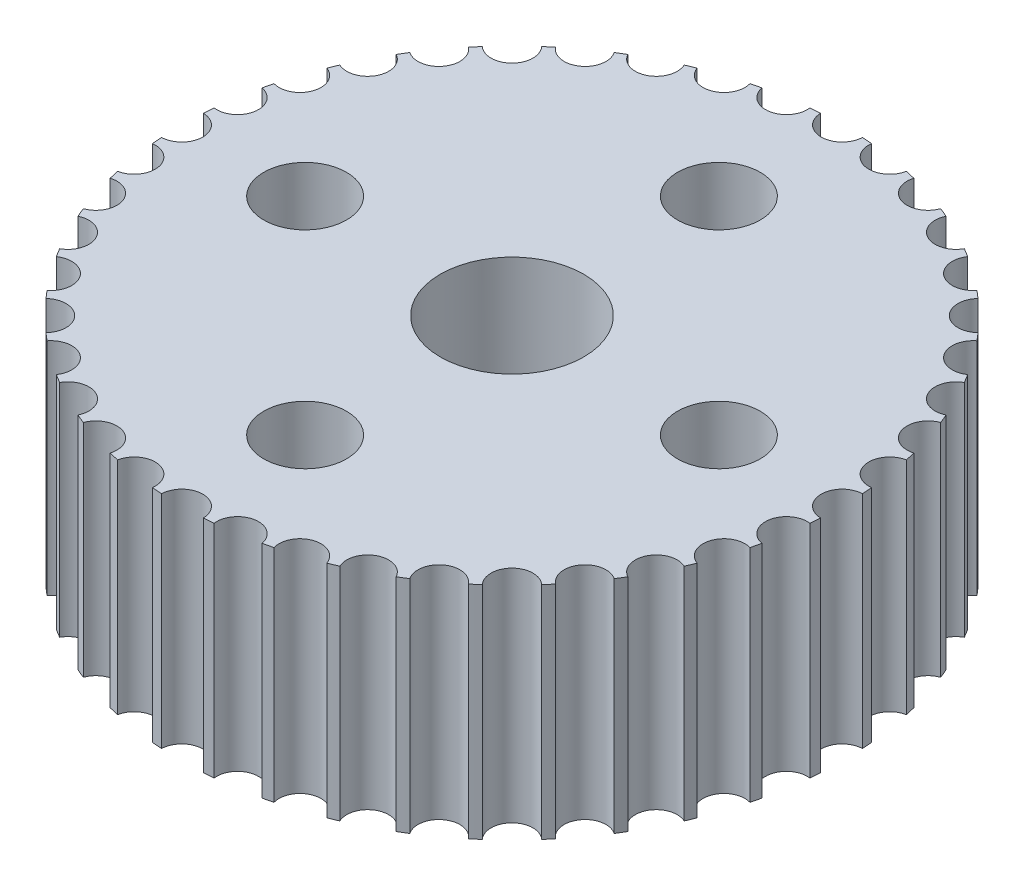
SolidWorks part; units mm, degrees
material "ABS"
ref_plane "Front Plane" through (0, 0, 0) normal (0, 0, 1) x (1, 0, 0)
ref_plane "Top Plane" through (0, 0, 0) normal (0, 1, 0) x (1, 0, 0)
ref_plane "Right Plane" through (0, 0, 0) normal (1, 0, 0) x (0, 0, -1)
sketch "Sketch1" plane through (0, 0, 0) normal (0, 1, 0) x (1, 0, 0)
  arc A0 (-2.619, 11.68) -> (-2.969, 11.5959) centre (0, 0) ccw
  arc A1 (-0.7596, 11.9459) -> (0.7596, 11.9459) centre (0, 11.97) ccw
  arc A2 (1.1185, 11.9176) -> (2.619, 11.68) centre (1.8725, 11.8226) ccw
  arc A3 (2.969, 11.5959) -> (4.4139, 11.1265) centre (3.6989, 11.3841) ccw
  arc A4 (4.7465, 10.9887) -> (6.1001, 10.299) centre (5.4343, 10.6653) ccw
  arc A5 (6.4071, 10.1109) -> (7.6362, 9.2179) centre (7.0358, 9.6839) ccw
  arc A6 (7.9099, 8.9841) -> (8.9841, 7.9099) centre (8.4641, 8.4641) ccw
  arc A7 (9.2179, 7.6362) -> (10.1109, 6.4071) centre (9.6839, 7.0358) ccw
  arc A8 (10.299, 6.1001) -> (10.9887, 4.7465) centre (10.6653, 5.4343) ccw
  arc A9 (11.1265, 4.4139) -> (11.5959, 2.969) centre (11.3841, 3.6989) ccw
  arc A10 (11.68, 2.619) -> (11.9176, 1.1185) centre (11.8226, 1.8725) ccw
  arc A11 (11.9459, 0.7596) -> (11.9459, -0.7596) centre (11.97, 0) ccw
  arc A12 (11.9176, -1.1185) -> (11.68, -2.619) centre (11.8226, -1.8725) ccw
  arc A13 (11.5959, -2.969) -> (11.1265, -4.4139) centre (11.3841, -3.6989) ccw
  arc A14 (10.9887, -4.7465) -> (10.299, -6.1001) centre (10.6653, -5.4343) ccw
  arc A15 (10.1109, -6.4071) -> (9.2179, -7.6362) centre (9.6839, -7.0358) ccw
  arc A16 (8.9841, -7.9099) -> (7.9099, -8.9841) centre (8.4641, -8.4641) ccw
  arc A17 (7.6362, -9.2179) -> (6.4071, -10.1109) centre (7.0358, -9.6839) ccw
  arc A18 (6.1001, -10.299) -> (4.7465, -10.9887) centre (5.4343, -10.6653) ccw
  arc A19 (4.4139, -11.1265) -> (2.969, -11.5959) centre (3.6989, -11.3841) ccw
  arc A20 (2.619, -11.68) -> (1.1185, -11.9176) centre (1.8725, -11.8226) ccw
  arc A21 (0.7596, -11.9459) -> (-0.7596, -11.9459) centre (0, -11.97) ccw
  arc A22 (-1.1185, -11.9176) -> (-2.619, -11.68) centre (-1.8725, -11.8226) ccw
  arc A23 (-2.969, -11.5959) -> (-4.4139, -11.1265) centre (-3.6989, -11.3841) ccw
  arc A24 (-4.7465, -10.9887) -> (-6.1001, -10.299) centre (-5.4343, -10.6653) ccw
  arc A25 (-6.4071, -10.1109) -> (-7.6362, -9.2179) centre (-7.0358, -9.6839) ccw
  arc A26 (-7.9099, -8.9841) -> (-8.9841, -7.9099) centre (-8.4641, -8.4641) ccw
  arc A27 (-9.2179, -7.6362) -> (-10.1109, -6.4071) centre (-9.6839, -7.0358) ccw
  arc A28 (-10.299, -6.1001) -> (-10.9887, -4.7465) centre (-10.6653, -5.4343) ccw
  arc A29 (-11.1265, -4.4139) -> (-11.5959, -2.969) centre (-11.3841, -3.6989) ccw
  arc A30 (-11.68, -2.619) -> (-11.9176, -1.1185) centre (-11.8226, -1.8725) ccw
  arc A31 (-11.9459, -0.7596) -> (-11.9459, 0.7596) centre (-11.97, 0) ccw
  arc A32 (-11.9176, 1.1185) -> (-11.68, 2.619) centre (-11.8226, 1.8725) ccw
  arc A33 (-11.5959, 2.969) -> (-11.1265, 4.4139) centre (-11.3841, 3.6989) ccw
  arc A34 (-10.9887, 4.7465) -> (-10.299, 6.1001) centre (-10.6653, 5.4343) ccw
  arc A35 (-10.1109, 6.4071) -> (-9.2179, 7.6362) centre (-9.6839, 7.0358) ccw
  arc A36 (-8.9841, 7.9099) -> (-7.9099, 8.9841) centre (-8.4641, 8.4641) ccw
  arc A37 (-7.6362, 9.2179) -> (-6.4071, 10.1109) centre (-7.0358, 9.6839) ccw
  arc A38 (-6.1001, 10.299) -> (-4.7465, 10.9887) centre (-5.4343, 10.6653) ccw
  arc A39 (-4.4139, 11.1265) -> (-2.969, 11.5959) centre (-3.6989, 11.3841) ccw
  arc A40 (-2.619, 11.68) -> (-1.1185, 11.9176) centre (-1.8725, 11.8226) ccw
  arc A41 (-0.7596, 11.9459) -> (-1.1185, 11.9176) centre (0, 0) ccw
  arc A42 (1.1185, 11.9176) -> (0.7596, 11.9459) centre (0, 0) ccw
  arc A43 (2.969, 11.5959) -> (2.619, 11.68) centre (0, 0) ccw
  arc A44 (4.7465, 10.9887) -> (4.4139, 11.1265) centre (0, 0) ccw
  arc A45 (6.4071, 10.1109) -> (6.1001, 10.299) centre (0, 0) ccw
  arc A46 (7.9099, 8.9841) -> (7.6362, 9.2179) centre (0, 0) ccw
  arc A47 (9.2179, 7.6362) -> (8.9841, 7.9099) centre (0, 0) ccw
  arc A48 (10.299, 6.1001) -> (10.1109, 6.4071) centre (0, 0) ccw
  arc A49 (11.1265, 4.4139) -> (10.9887, 4.7465) centre (0, 0) ccw
  arc A50 (11.68, 2.619) -> (11.5959, 2.969) centre (0, 0) ccw
  arc A51 (11.9459, 0.7596) -> (11.9176, 1.1185) centre (0, 0) ccw
  arc A52 (11.9176, -1.1185) -> (11.9459, -0.7596) centre (0, 0) ccw
  arc A53 (11.5959, -2.969) -> (11.68, -2.619) centre (0, 0) ccw
  arc A54 (10.9887, -4.7465) -> (11.1265, -4.4139) centre (0, 0) ccw
  arc A55 (10.1109, -6.4071) -> (10.299, -6.1001) centre (0, 0) ccw
  arc A56 (8.9841, -7.9099) -> (9.2179, -7.6362) centre (0, 0) ccw
  arc A57 (7.6362, -9.2179) -> (7.9099, -8.9841) centre (0, 0) ccw
  arc A58 (6.1001, -10.299) -> (6.4071, -10.1109) centre (0, 0) ccw
  arc A59 (4.4139, -11.1265) -> (4.7465, -10.9887) centre (0, 0) ccw
  arc A60 (2.619, -11.68) -> (2.969, -11.5959) centre (0, 0) ccw
  arc A61 (0.7596, -11.9459) -> (1.1185, -11.9176) centre (0, 0) ccw
  arc A62 (-1.1185, -11.9176) -> (-0.7596, -11.9459) centre (0, 0) ccw
  arc A63 (-2.969, -11.5959) -> (-2.619, -11.68) centre (0, 0) ccw
  arc A64 (-4.7465, -10.9887) -> (-4.4139, -11.1265) centre (0, 0) ccw
  arc A65 (-6.4071, -10.1109) -> (-6.1001, -10.299) centre (0, 0) ccw
  arc A66 (-7.9099, -8.9841) -> (-7.6362, -9.2179) centre (0, 0) ccw
  arc A67 (-9.2179, -7.6362) -> (-8.9841, -7.9099) centre (0, 0) ccw
  arc A68 (-10.299, -6.1001) -> (-10.1109, -6.4071) centre (0, 0) ccw
  arc A69 (-11.1265, -4.4139) -> (-10.9887, -4.7465) centre (0, 0) ccw
  arc A70 (-11.68, -2.619) -> (-11.5959, -2.969) centre (0, 0) ccw
  arc A71 (-11.9459, -0.7596) -> (-11.9176, -1.1185) centre (0, 0) ccw
  arc A72 (-11.9176, 1.1185) -> (-11.9459, 0.7596) centre (0, 0) ccw
  arc A73 (-11.5959, 2.969) -> (-11.68, 2.619) centre (0, 0) ccw
  arc A74 (-10.9887, 4.7465) -> (-11.1265, 4.4139) centre (0, 0) ccw
  arc A75 (-10.1109, 6.4071) -> (-10.299, 6.1001) centre (0, 0) ccw
  arc A76 (-8.9841, 7.9099) -> (-9.2179, 7.6362) centre (0, 0) ccw
  arc A77 (-7.6362, 9.2179) -> (-7.9099, 8.9841) centre (0, 0) ccw
  arc A78 (-6.1001, 10.299) -> (-6.4071, 10.1109) centre (0, 0) ccw
  arc A79 (-4.4139, 11.1265) -> (-4.7465, 10.9887) centre (0, 0) ccw
  point P86 (0, 0)
  dimension "D1" = 23.94
  dimension "D2" = 1.52
  dimension "D3" = 40
extrude "Boss-Extrude1" add sketch "Sketch1" along normal blind 8
sketch "Sketch2" plane through (0, 8, 0) normal (0, 1, 0) x (1, 0, 0)
  circle A0 centre (0, 0) radius 15
  dimension "D1" = 30
sketch "Sketch4" plane through (0, 0, 0) normal (0, -1, 0) x (1, 0, 0)
  line L0 (0, 0) -> (0, 7.5) construction
  circle A0 centre (0, 0) radius 2.6
  point P4 (-5.631, -4.954)
  point P8 (5.9449, -4.5725)
  point P9 (0, 7.5)
  dimension "D1" = 5.2
  dimension "D8" = 7.5
extrude "Cut-Extrude1" cut sketch "Sketch4" against normal blind 23
sketch "Sketch5" plane through (0, 0, 0) normal (0, -1, 0) x (1, 0, 0)
  circle A0 centre (0, 7.5) radius 1.5
  circle A1 centre (7.5, 0) radius 1.5
  circle A2 centre (0, -7.5) radius 1.5
  circle A3 centre (-7.5, 0) radius 1.5
  dimension "D1" = 3
  dimension "D2" = 7.5
  dimension "D4" = 7.5
  dimension "D3" = 4
extrude "Cut-Extrude2" cut sketch "Sketch5" against normal through all
